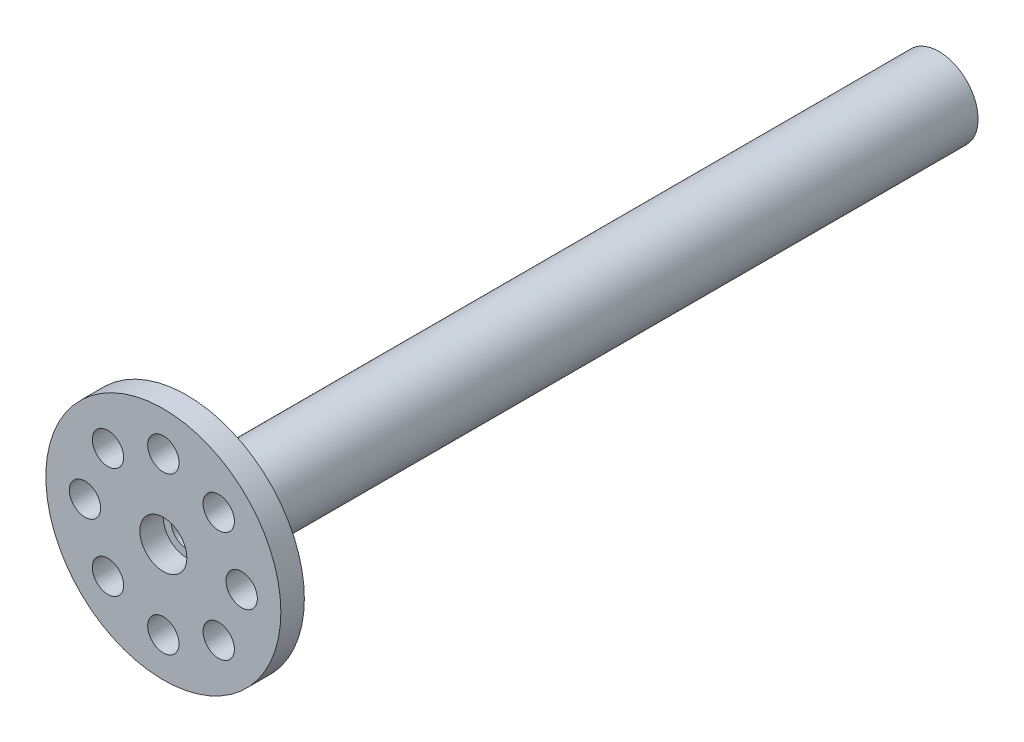
SolidWorks part; units mm, degrees
material "1060 合金"
ref_plane "前视基准面" through (0, 0, 0) normal (0, 0, 1) x (1, 0, 0)
ref_plane "上视基准面" through (0, 0, 0) normal (0, 1, 0) x (1, 0, 0)
ref_plane "右视基准面" through (0, 0, 0) normal (1, 0, 0) x (0, 0, -1)
sketch "草图1" plane through (0, 0, 0) normal (0, 0, 1) x (1, 0, 0)
  circle A0 centre (0, 0) radius 5
  dimension "D1" = 10
extrude "凸台-拉伸1" add sketch "草图1" along normal blind 93
sketch "草图2" plane through (0, 0, 93) normal (0, 0, 1) x (1, 0, 0)
  circle A0 centre (0, 0) radius 6
  dimension "D1" = 12
extrude "凸台-拉伸2" add sketch "草图2" along normal blind 3
sketch "草图3" plane through (0, 0, 96) normal (0, 0, 1) x (1, 0, 0)
  line L0 (10, 0) -> (0, 0) construction
  line L1 (0, 0) -> (7.0711, 7.0711) construction
  circle A0 centre (0, 0) radius 15
  circle A1 centre (0, 0) radius 10 construction
  circle A2 centre (0, 10) radius 2
  circle A3 centre (10, 0) radius 2
  circle A4 centre (0, -10) radius 2
  circle A5 centre (-10, 0) radius 2
  circle A6 centre (7.0711, 7.0711) radius 2
  circle A7 centre (7.0711, -7.0711) radius 2
  circle A8 centre (-7.0711, -7.0711) radius 2
  circle A9 centre (-7.0711, 7.0711) radius 2
  point P23 (0, 0)
  dimension "D1" = 30
  dimension "D2" = 20
  dimension "D3" = 4
  dimension "D4" = 4
  dimension "D5" = 4
  dimension "D6" = 4
  dimension "D8" = 4
  dimension "D7" = 45
  dimension "D9" = 4
extrude "凸台-拉伸3" add sketch "草图3" along normal blind 3
sketch "草图6" plane through (0, 0, 0) normal (0, 0, -1) x (-1, 0, 0)
  circle A0 centre (0, 0) radius 2
  dimension "D1" = 4
extrude "切除-拉伸3" cut sketch "草图6" against normal through all
sketch "草图7" plane through (0, 0, 99) normal (0, 0, 1) x (1, 0, 0)
  circle A0 centre (0, 0) radius 3
  dimension "D1" = 6
extrude "切除-拉伸4" cut sketch "草图7" against normal blind 3
